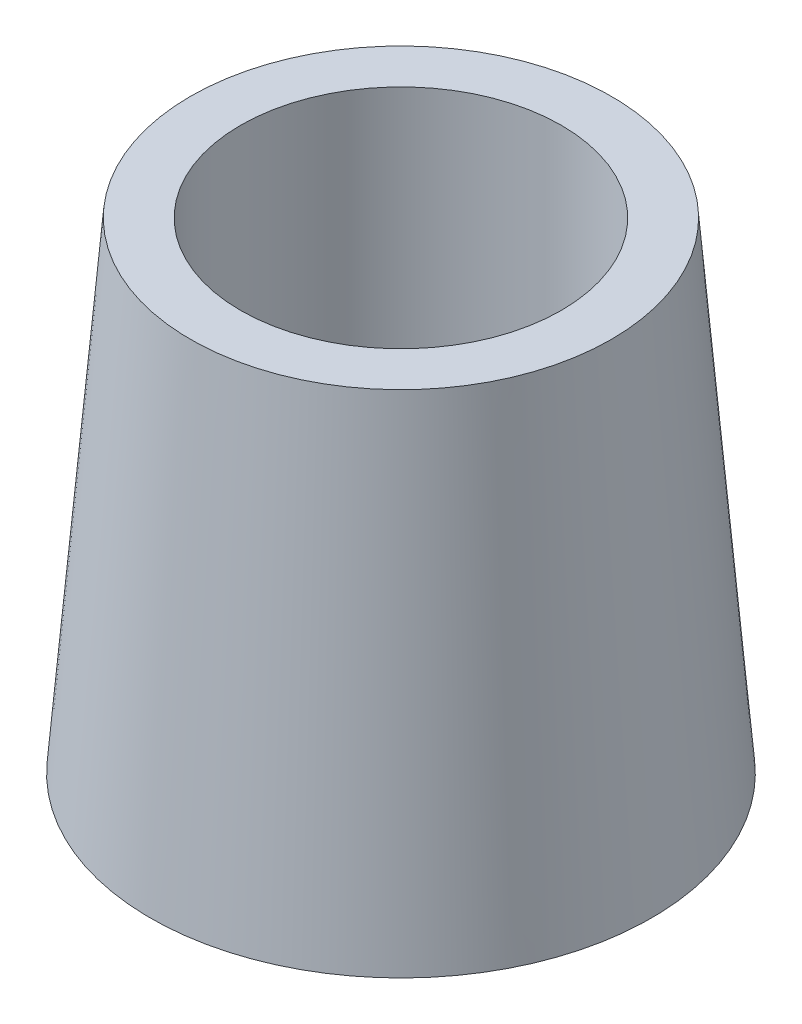
SolidWorks part; units mm, degrees
material "Cast Carbon Steel"
ref_plane "Front Plane" through (0, 0, 0) normal (0, 0, 1) x (1, 0, 0)
ref_plane "Top Plane" through (0, 0, 0) normal (0, 1, 0) x (1, 0, 0)
ref_plane "Right Plane" through (0, 0, 0) normal (1, 0, 0) x (0, 0, -1)
sketch "Sketch1" plane through (0, 0, 0) normal (0, 0, 1) x (1, 0, 0)
  line L0 (0, 0) -> (-12.5, 0)
  line L1 (-12.5, 0) -> (-10.5, 24)
  line L2 (-10.5, 24) -> (0, 24)
  line L3 (0, 24) -> (0, 0)
  dimension "D1" = 12.5
  dimension "D2" = 10.5
  dimension "D3" = 24
revolve "Revolve1" add sketch "Sketch1" angle 360 about L3
sketch "Sketch2" plane through (0, 24, 0) normal (0, 1, 0) x (1, 0, 0)
  circle A0 centre (0, 0) radius 8
  dimension "D1" = 16
extrude "Cut-Extrude1" cut sketch "Sketch2" against normal through all and the other way through all
